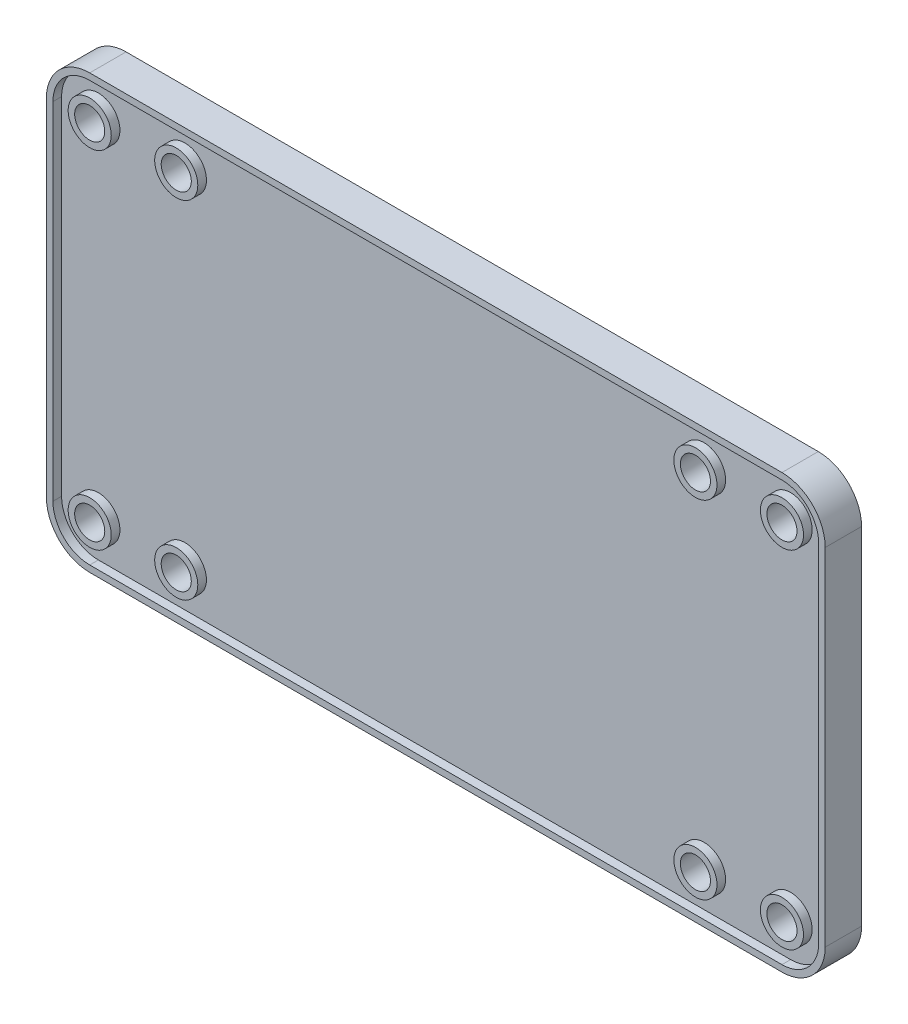
SolidWorks part; units mm, degrees
material "ABS"
ref_plane "Front Plane" through (0, 0, 0) normal (0, 0, 1) x (1, 0, 0)
ref_plane "Top Plane" through (0, 0, 0) normal (0, 1, 0) x (1, 0, 0)
ref_plane "Right Plane" through (0, 0, 0) normal (1, 0, 0) x (0, 0, -1)
sketch "Sketch1" plane through (0, 0, 0) normal (0, 0, 1) x (1, 0, 0)
  line L0 (-57.15, 0) -> (57.15, 0) construction
  line L1 (-50.8, -31.75) -> (50.8, -31.75)
  line L2 (-57.15, -25.4) -> (-57.15, 25.4)
  line L3 (-50.8, 31.75) -> (50.8, 31.75)
  line L4 (57.15, -25.4) -> (57.15, 25.4)
  line L5 (-57.15, -31.75) -> (57.15, 31.75) construction
  line L6 (-57.15, 31.75) -> (57.15, -31.75) construction
  line L7 (0, 31.75) -> (0, -31.75) construction
  arc A0 (50.8, 31.75) -> (57.15, 25.4) centre (50.8, 25.4) cw
  arc A1 (50.8, -31.75) -> (57.15, -25.4) centre (50.8, -25.4) ccw
  arc A2 (-50.8, -31.75) -> (-57.15, -25.4) centre (-50.8, -25.4) cw
  arc A3 (-57.15, 25.4) -> (-50.8, 31.75) centre (-50.8, 25.4) cw
  circle A4 centre (-50.8, -25.4) radius 2.2098
  circle A5 centre (-38.1, -25.4) radius 2.2098
  circle A6 centre (-50.8, 25.4) radius 2.2098
  circle A7 centre (-38.1, 25.4) radius 2.2098
  circle A8 centre (50.8, 25.4) radius 2.2098
  circle A9 centre (38.1, 25.4) radius 2.2098
  circle A10 centre (50.8, -25.4) radius 2.2098
  circle A11 centre (38.1, -25.4) radius 2.2098
  point P0 (0, 0)
  dimension "D3" = 6.35
  dimension "D4" = 4.4196
  dimension "D1" = 63.5
  dimension "D2" = 114.3
  dimension "D5" = 6.35
  dimension "D6" = 12.7
  dimension "D7" = 6.35
extrude "Boss-Extrude1" add sketch "Sketch1" against normal blind 3.175
sketch "Sketch2" plane through (0, 0, 0) normal (0, 0, 1) x (1, 0, 0)
  line L12 (50.8, 30.7975) -> (-50.8, 30.7975)
  line L13 (-56.1975, 25.4) -> (-56.1975, -25.4)
  line L14 (-50.8, -30.7975) -> (50.8, -30.7975)
  line L15 (56.1975, -25.4) -> (56.1975, 25.4)
  line L16 (50.8, 30.7975) -> (-50.8, 30.7975)
  line L17 (-56.1975, 25.4) -> (-56.1975, -25.4)
  line L18 (-50.8, -30.7975) -> (50.8, -30.7975)
  line L19 (56.1975, -25.4) -> (56.1975, 25.4)
  circle A0 centre (-50.8, -25.4) radius 2.2098 construction
  arc A8 (56.1975, 25.4) -> (50.8, 30.7975) centre (50.8, 25.4) ccw
  arc A9 (-50.8, 30.7975) -> (-56.1975, 25.4) centre (-50.8, 25.4) ccw
  arc A10 (-56.1975, -25.4) -> (-50.8, -30.7975) centre (-50.8, -25.4) ccw
  arc A11 (50.8, -30.7975) -> (56.1975, -25.4) centre (50.8, -25.4) ccw
  arc A12 (56.1975, 25.4) -> (50.8, 30.7975) centre (50.8, 25.4) ccw
  arc A13 (-50.8, 30.7975) -> (-56.1975, 25.4) centre (-50.8, 25.4) ccw
  arc A14 (-56.1975, -25.4) -> (-50.8, -30.7975) centre (-50.8, -25.4) ccw
  arc A15 (50.8, -30.7975) -> (56.1975, -25.4) centre (50.8, -25.4) ccw
  circle A36 centre (38.1, 25.4) radius 3.1623
  circle A37 centre (50.8, 25.4) radius 3.1623
  circle A38 centre (50.8, -25.4) radius 3.1623
  circle A39 centre (38.1, -25.4) radius 3.1623
  circle A40 centre (-38.1, -25.4) radius 3.1623
  circle A41 centre (-50.8, -25.4) radius 3.1623
  circle A42 centre (-38.1, 25.4) radius 3.1623
  circle A43 centre (-50.8, 25.4) radius 3.1623
  circle A44 centre (-38.1, -25.4) radius 2.2098 construction
  circle A47 centre (38.1, -25.4) radius 2.2098 construction
  circle A50 centre (50.8, -25.4) radius 2.2098 construction
  circle A51 centre (50.8, 25.4) radius 2.2098 construction
  circle A52 centre (38.1, 25.4) radius 2.2098 construction
  circle A53 centre (-38.1, 25.4) radius 2.2098 construction
  circle A54 centre (-50.8, 25.4) radius 2.2098 construction
  dimension "D2" = 0.9525
  dimension "D1" = 0.9525
extrude "Cut-Extrude3" cut sketch "Sketch2" against normal blind 1.27
sketch "Sketch3" plane through (0, 0, -3.175) normal (0, 0, -1) x (-1, 0, 0)
  line L4 (-57.15, 25.4) -> (-57.15, -25.4)
  line L5 (-50.8, -31.75) -> (50.8, -31.75)
  line L6 (57.15, -25.4) -> (57.15, 25.4)
  line L7 (50.8, 31.75) -> (-50.8, 31.75)
  line L8 (-57.15, 25.4) -> (-57.15, -25.4)
  line L9 (-50.8, -31.75) -> (50.8, -31.75)
  line L10 (57.15, -25.4) -> (57.15, 25.4)
  line L11 (50.8, 31.75) -> (-50.8, 31.75)
  circle A0 centre (-50.8, -25.4) radius 2.2098 construction
  circle A1 centre (-38.1, -25.4) radius 2.2098 construction
  circle A2 centre (38.1, -25.4) radius 2.2098 construction
  circle A3 centre (50.8, -25.4) radius 2.2098 construction
  arc A4 (-50.8, 31.75) -> (-57.15, 25.4) centre (-50.8, 25.4) ccw
  arc A5 (-57.15, -25.4) -> (-50.8, -31.75) centre (-50.8, -25.4) ccw
  arc A6 (50.8, -31.75) -> (57.15, -25.4) centre (50.8, -25.4) ccw
  arc A7 (57.15, 25.4) -> (50.8, 31.75) centre (50.8, 25.4) ccw
  arc A8 (-50.8, 31.75) -> (-57.15, 25.4) centre (-50.8, 25.4) ccw
  arc A9 (-57.15, -25.4) -> (-50.8, -31.75) centre (-50.8, -25.4) ccw
  arc A10 (50.8, -31.75) -> (57.15, -25.4) centre (50.8, -25.4) ccw
  arc A11 (57.15, 25.4) -> (50.8, 31.75) centre (50.8, 25.4) ccw
  circle A12 centre (50.8, 25.4) radius 2.2098 construction
  circle A13 centre (38.1, 25.4) radius 2.2098 construction
  circle A14 centre (-38.1, 25.4) radius 2.2098 construction
  circle A15 centre (-50.8, 25.4) radius 2.2098 construction
  circle A16 centre (-50.8, -25.4) radius 2.2098
  circle A17 centre (-38.1, -25.4) radius 2.2098
  circle A18 centre (38.1, -25.4) radius 2.2098
  circle A19 centre (50.8, -25.4) radius 2.2098
  circle A20 centre (50.8, 25.4) radius 2.2098
  circle A21 centre (38.1, 25.4) radius 2.2098
  circle A22 centre (-38.1, 25.4) radius 2.2098
  circle A23 centre (-50.8, 25.4) radius 2.2098
  circle A24 centre (0, 0) radius 5.08
  circle A25 centre (38.1, 0) radius 5.08
  circle A26 centre (-38.1, 0) radius 5.08
  dimension "D2" = 10.16
extrude "Boss-Extrude2" add sketch "Sketch3" along normal blind 2.159
equation "\"tolerance\"= 0.005"
equation "\"D4@Sketch1\"=0.164 + \"tolerance\" * 2"
equation "\"D2@Sketch3\"=.39 + \"tolerance\" * 2"
equation "\"D1@Boss-Extrude2\"= 0.080000in + \"tolerance\""
